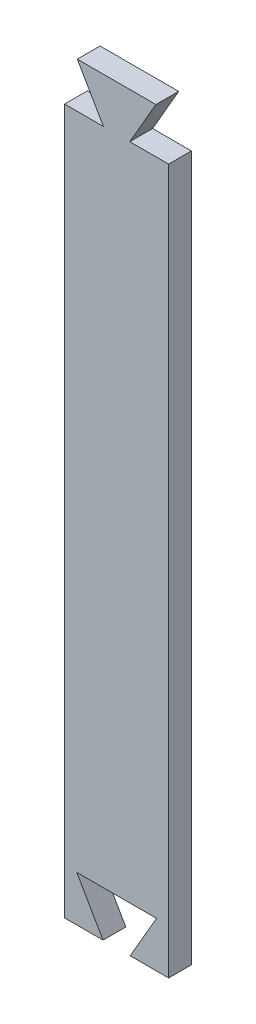
SolidWorks part; units mm, degrees
material "Custom Plastic"
ref_plane "X-Y Datum" through (0, 0, 0) normal (0, 0, 1) x (1, 0, 0)
ref_plane "X-Z Datum" through (0, 0, 0) normal (0, 1, 0) x (1, 0, 0)
ref_plane "Y-Z Datum" through (0, 0, 0) normal (1, 0, 0) x (0, 0, -1)
sketch "Sketch1" plane through (0, 0, 0) normal (0, 0, 1) x (1, 0, 0)
  line L0 (-3.0241, 0) -> (-8.89, 10.16)
  line L1 (-8.89, 10.16) -> (8.89, 10.16)
  line L2 (8.89, 10.16) -> (3.0241, 0)
  line L3 (3.0241, 0) -> (11.5976, 0)
  line L4 (11.5976, 0) -> (11.5976, 157.1625)
  line L5 (-3.0241, 0) -> (-11.5976, 0)
  line L6 (-11.5976, 0) -> (-11.5976, 157.1625)
  line L7 (-11.5976, 0) -> (11.5976, 0) construction
  line L8 (11.5976, 157.1625) -> (2.9411, 157.1625)
  line L9 (-11.5976, 78.5812) -> (11.5976, 78.5812) construction
  line L13 (-2.9411, 157.1625) -> (-11.5976, 157.1625)
  line L14 (-2.9411, 157.1625) -> (-8.763, 167.2463)
  line L15 (-8.763, 167.2463) -> (8.763, 167.2463)
  line L16 (8.763, 167.2463) -> (2.9411, 157.1625)
  line L17 (0, 167.2463) -> (0, 78.5812) construction
  point P7 (0, 0)
  point P9 (0, 10.16)
  dimension "D1" = 60
  dimension "D2" = 10.16
  dimension "D3" = 60
  dimension "D4" = 17.78
  dimension "D5" = 23.1952
  dimension "D6" = 157.1625
  dimension "D7" = 60
  dimension "D8" = 60
  dimension "D9" = 10.0838
  dimension "D10" = 17.526
extrude "Boss-Extrude1" add sketch "Sketch1" along normal blind 5.08
